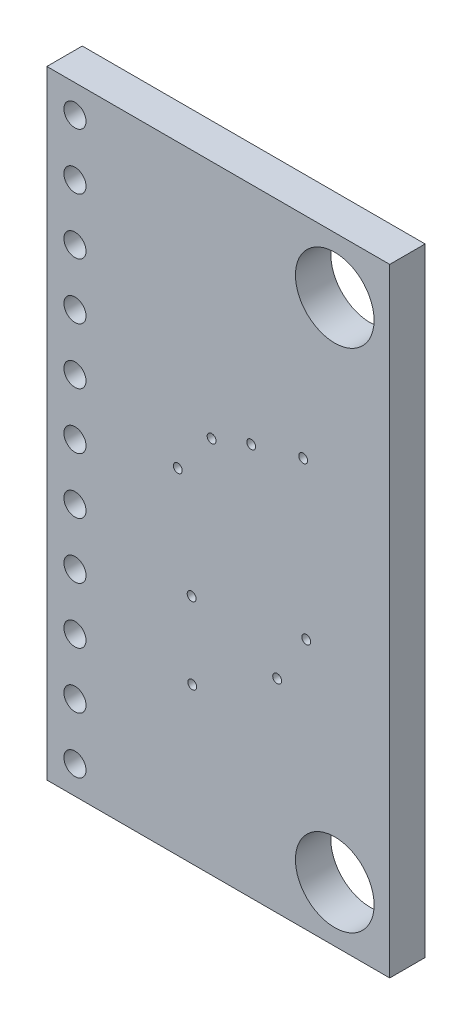
SolidWorks part; units mm, degrees
ref_plane "Front Plane" through (0, 0, 0) normal (0, 0, 1) x (1, 0, 0)
ref_plane "Top Plane" through (0, 0, 0) normal (0, 1, 0) x (1, 0, 0)
ref_plane "Right Plane" through (0, 0, 0) normal (1, 0, 0) x (0, 0, -1)
sketch "Sketch1" plane through (0, 0, 0) normal (0, 0, 1) x (1, 0, 0)
  line L1 (-7.75, -13.97) -> (7.75, -13.97)
  line L2 (-7.75, -13.97) -> (-7.75, 13.97)
  line L3 (-7.75, 13.97) -> (7.75, 13.97)
  line L4 (7.75, -13.97) -> (7.75, 13.97)
  line L5 (-7.75, -13.97) -> (7.75, 13.97) construction
  line L6 (-7.75, 13.97) -> (7.75, -13.97) construction
  point P0 (0, 0)
  dimension "D1" = 15.5
  dimension "D2" = 27.94
extrude "Boss-Extrude1" add sketch "Sketch1" along normal blind 1.6
sketch "Sketch2" plane through (0, 0, 1.6) normal (0, 0, 1) x (1, 0, 0)
  line L0 (-7.75, -13.97) -> (7.75, -13.97) construction
  line L1 (-7.75, 13.97) -> (-7.75, -13.97) construction
  circle A0 centre (-6.48, -12.7) radius 0.5
  circle A1 centre (-6.48, -10.16) radius 0.5
  circle A2 centre (-6.48, -7.62) radius 0.5
  circle A3 centre (-6.48, -5.08) radius 0.5
  circle A4 centre (-6.48, -2.54) radius 0.5
  circle A5 centre (-6.48, 0) radius 0.5
  circle A6 centre (-6.48, 2.54) radius 0.5
  circle A7 centre (-6.48, 5.08) radius 0.5
  circle A8 centre (-6.48, 7.62) radius 0.5
  circle A9 centre (-6.48, 10.16) radius 0.5
  circle A10 centre (-6.48, 12.7) radius 0.5
  circle A11 centre (5.2641, 11.4235) radius 1.778
  circle A12 centre (5.2641, -11.4641) radius 1.778
  dimension "D1" = 1
  dimension "D3" = 1.27
  dimension "D5" = 3.556
  dimension "D2" = 1.27
  dimension "D4" = 11
extrude "Cut-Extrude1" cut sketch "Sketch2" against normal blind 2
sketch "Sketch3" plane through (0, 0, 1.6) normal (0, 0, 1) x (1, 0, 0)
  circle A0 centre (-1.8307, 1.2025) radius 0.2
  circle A1 centre (-0.3024, 3.1256) radius 0.2
  circle A2 centre (1.4868, 3.7915) radius 0.2
  circle A3 centre (3.837, 4.4236) radius 0.2
  circle A4 centre (3.9757, -2.6015) radius 0.2
  circle A5 centre (2.6591, -4.7909) radius 0.2
  circle A6 centre (-1.1775, -6.9449) radius 0.2
  circle A7 centre (-1.2058, -3.5005) radius 0.2
  dimension "D1" = 0.4
extrude "Cut-Extrude2" cut sketch "Sketch3" against normal blind 10
